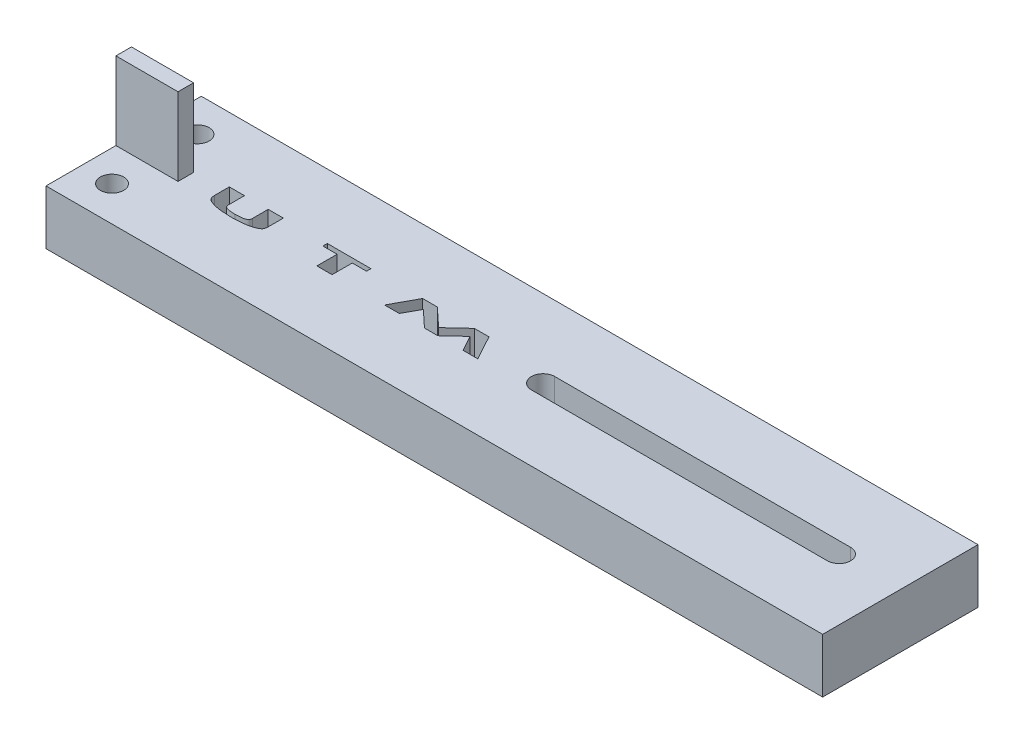
SolidWorks part; units mm, degrees
ref_plane "Front Plane" through (0, 0, 0) normal (0, 0, 1) x (1, 0, 0)
ref_plane "Top Plane" through (0, 0, 0) normal (0, 1, 0) x (1, 0, 0)
ref_plane "Right Plane" through (0, 0, 0) normal (1, 0, 0) x (0, 0, -1)
sketch "Sketch1" plane through (0, 0, 0) normal (0, 1, 0) x (1, 0, 0)
  line L1 (-50, 10) -> (50, 10)
  line L2 (-50, 10) -> (-50, -10)
  line L3 (-50, -10) -> (50, -10)
  line L4 (50, 10) -> (50, -10)
  line L5 (-50, 10) -> (50, -10) construction
  line L6 (-50, -10) -> (50, 10) construction
  point P0 (0, 0)
  dimension "D1" = 20
  dimension "D2" = 100
extrude "Boss-Extrude1" add sketch "Sketch1" along normal blind 7
sketch "Sketch2" plane through (0, 7, 0) normal (0, 1, 0) x (1, 0, 0)
  line L0 (-50, 0) -> (50, 0) construction
  line L1 (-50, 10) -> (-50, -10) construction
  line L2 (50, -10) -> (50, 10) construction
  line L3 (-50, 0) -> (-50, 1) construction
  line L4 (-50, 0) -> (-50, -1) construction
  line L5 (-50, -1) -> (-50, 1)
  line L6 (-50, -1) -> (-42, -1)
  line L7 (-50, 1) -> (-42, 1)
  line L8 (-42, -1) -> (-42, 1)
  dimension "D1" = 1
  dimension "D2" = 1
  dimension "D3" = 8
  dimension "D4" = 2
extrude "Boss-Extrude2" add sketch "Sketch2" along normal blind 10
sketch "Sketch3" plane through (-50, 0, 0) normal (-1, 0, 0) x (0, 0, 1)
  line L0 (1, 7) -> (-1, 7) construction
  line L1 (0, 7) -> (0, 15.2) construction
  line L4 (-0.6, 15.2) -> (0.6, 15.2)
  line L5 (-0.6, 15.2) -> (-0.6, 7)
  line L6 (-0.6, 7) -> (0.6, 7)
  line L7 (0.6, 15.2) -> (0.6, 7)
  line L8 (-0.6, 15.2) -> (0.6, 7) construction
  line L9 (-0.6, 7) -> (0.6, 15.2) construction
  point P8 (0, 11.1)
  point P13 (0, 0)
  dimension "D1" = 1.2
  dimension "D2" = 8.2
extrude "Cut-Extrude1" cut sketch "Sketch3" against normal blind 6.5
sketch "Sketch4" plane through (0, 7, 0) normal (0, 1, 0) x (1, 0, 0)
  line L1 (50, 10) -> (-50, 10) construction
  line L2 (-46, 1) -> (-46, 10) construction
  line L3 (-42, 1) -> (-50, 1) construction
  line L4 (-46, -1) -> (-46, -10) construction
  line L5 (-50, -1) -> (-42, -1) construction
  line L6 (-50, -10) -> (50, -10) construction
  circle A0 centre (-46, -5.5) radius 1.5
  circle A1 centre (-46, 5.5) radius 1.5
  dimension "D1" = 3
  dimension "3" = 3
extrude "Cut-Extrude2" cut sketch "Sketch4" against normal blind 16.5
sketch "Sketch5" plane through (0, 7, 0) normal (0, 1, 0) x (1, 0, 0)
  line L0 (-42, 0) -> (50, 0) construction
  line L1 (-42, -1) -> (-42, 1) construction
  line L2 (50, -10) -> (50, 10) construction
  line L3 (4, 0) -> (42.1045, 0) construction
  line L4 (4, 1.5) -> (42.1045, 1.5)
  line L5 (4, -1.5) -> (42.1045, -1.5)
  arc A0 (4, 1.5) -> (4, -1.5) centre (4, 0) ccw
  arc A1 (42.1045, -1.5) -> (42.1045, 1.5) centre (42.1045, 0) ccw
  point P8 (23.0523, 0)
extrude "Cut-Extrude3" cut sketch "Sketch5" against normal blind 16.5
sketch "Sketch6" plane through (0, 7, 0) normal (0, 1, 0) x (1, 0, 0)
  text T0 "<b>UTM</b>" font "Century Gothic" height 3.175
extrude "Cut-Extrude4" cut sketch "Sketch6" against normal blind 16.5
